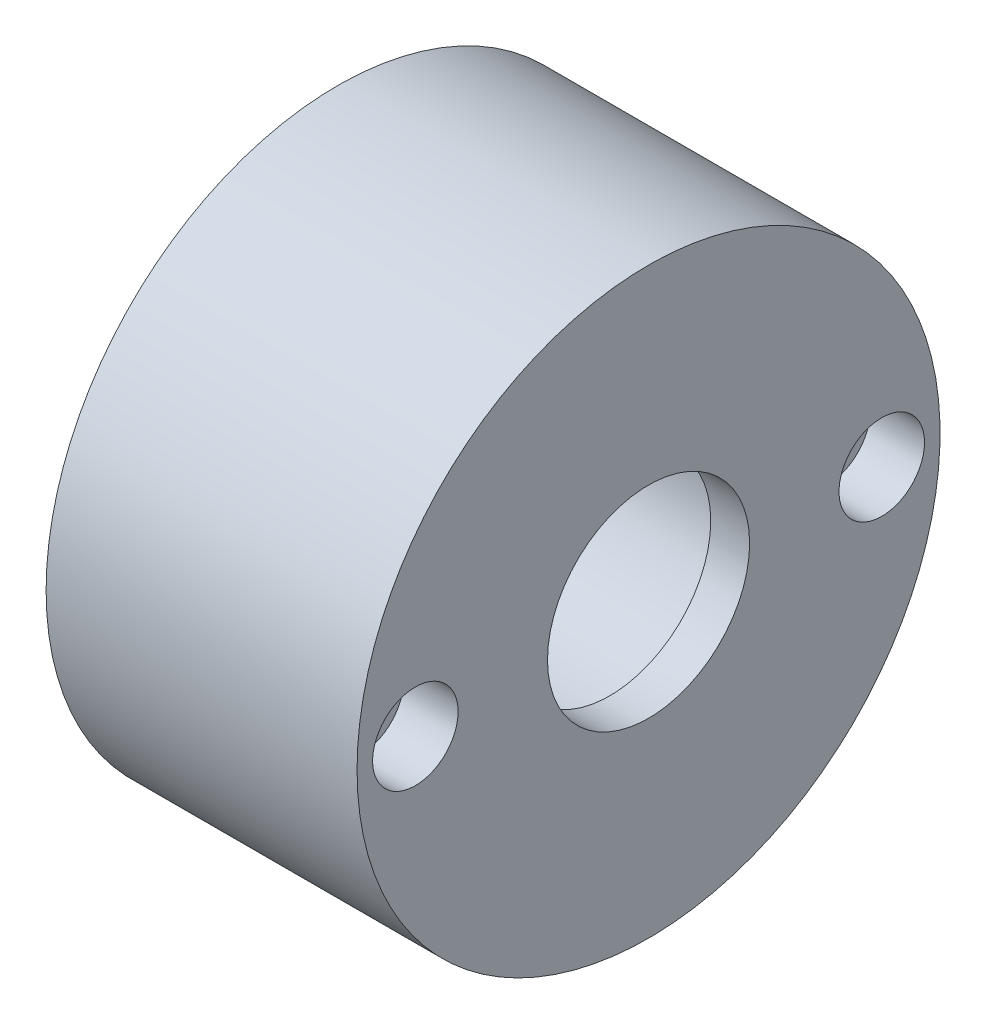
SolidWorks part; units mm, degrees
ref_plane "正面" through (0, 0, 0) normal (0, 0, 1) x (1, 0, 0)
ref_plane "平面" through (0, 0, 0) normal (0, 1, 0) x (1, 0, 0)
ref_plane "右側面" through (0, 0, 0) normal (1, 0, 0) x (0, 0, -1)
sketch "ｽｹｯﾁ1" plane through (0, 0, 0) normal (0, 0, 1) x (1, 0, 0)
  line L0 (-40, 16.5) -> (-5, 16.5)
  line L1 (-5, 16.5) -> (-5, 13)
  line L2 (-5, 13) -> (0, 13)
  line L3 (0, 13) -> (0, 37.5)
  line L4 (0, 37.5) -> (-40, 37.5)
  line L5 (-40, 37.5) -> (-40, 16.5)
  line L6 (-40, 0) -> (0, 0) construction
revolve "回転1" add sketch "ｽｹｯﾁ1" angle 360 about L6
sketch "ｽｹｯﾁ2" plane through (0, 0, 0) normal (1, 0, 0) x (0, 0, -1)
  circle A0 centre (30, 0) radius 4
  circle A1 centre (-30, 0) radius 4
extrude "ｶｯﾄ - 押し出し1" cut sketch "ｽｹｯﾁ2" against normal through all and the other way through all
sketch "ｽｹｯﾁ3" plane through (0, 0, 0) normal (1, 0, 0) x (0, 0, -1)
  circle A0 centre (30, 0) radius 5.5
  circle A1 centre (-30, 0) radius 5.5
extrude "ｶｯﾄ - 押し出し2" cut sketch "ｽｹｯﾁ3" against normal blind 7
